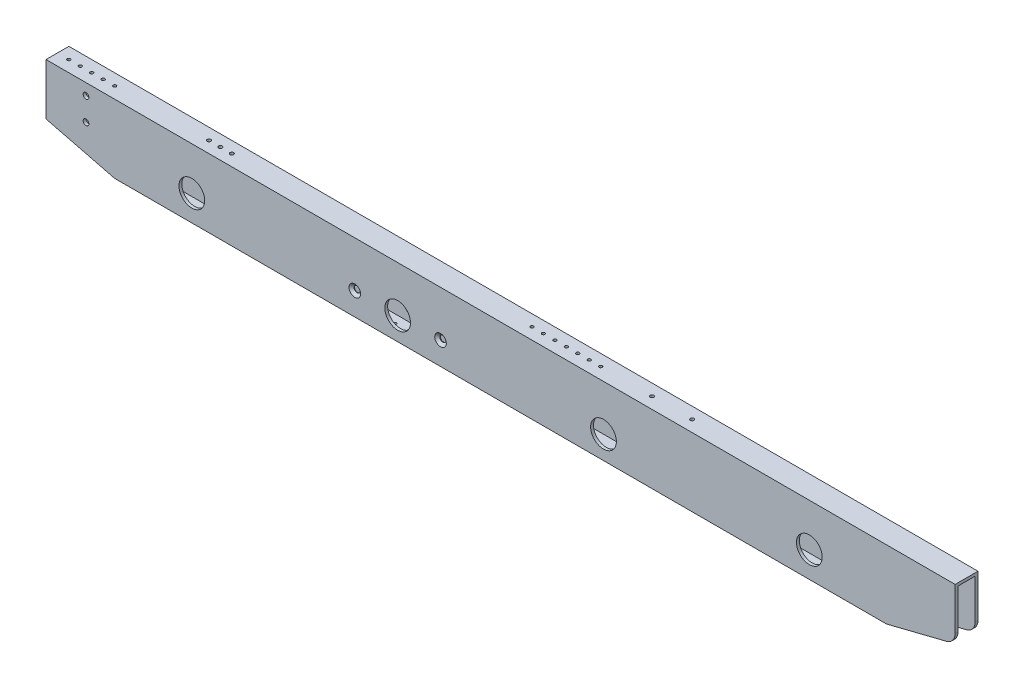
SolidWorks part; units mm, degrees
ref_plane "Front Plane" through (0, 0, 0) normal (0, 0, 1) x (1, 0, 0)
ref_plane "Top Plane" through (0, 0, 0) normal (0, 1, 0) x (1, 0, 0)
ref_plane "Right Plane" through (0, 0, 0) normal (1, 0, 0) x (0, 0, -1)
sketch "Sketch1" plane through (0, 0, 0) normal (0, 0, 1) x (1, 0, 0)
  line L0 (0, -12.7) -> (-342.9, -9.525) construction
  line L1 (-504.825, 38.1) -> (504.825, 38.1)
  line L2 (-504.825, 38.1) -> (-504.825, -38.1)
  line L3 (-504.825, -38.1) -> (504.825, -38.1)
  line L4 (504.825, 38.1) -> (504.825, -38.1)
  line L5 (-504.825, 38.1) -> (504.825, -38.1) construction
  line L6 (-504.825, -38.1) -> (504.825, 38.1) construction
  line L7 (-504.825, -38.1) -> (504.825, -38.1) construction
  line L8 (-504.825, -38.1) -> (-504.825, -12.7) construction
  line L9 (-327.025, -63.5) -> (327.025, -63.5) construction
  line L10 (-504.825, -12.7) -> (504.825, -12.7) construction
  line L11 (504.825, -38.1) -> (504.825, -12.7) construction
  line L12 (0, -12.7) -> (342.9, -9.525) construction
  line L13 (-114.3, -12.7) -> (114.3, -12.7) construction
  circle A0 centre (114.3, -12.7) radius 14.2875
  circle A1 centre (-342.9, -9.525) radius 14.2875
  circle A2 centre (342.9, -9.525) radius 14.2875
  circle A3 centre (-114.3, -12.7) radius 14.2875
  point P0 (0, 0)
  dimension "D5" = 28.575
  dimension "D4" = 28.575
  dimension "D8" = 228.6
  dimension "D6" = 228.6
  dimension "D7" = 228.6
  dimension "D1" = 76.2
  dimension "D2" = 1009.65
  dimension "D3" = 25.4
extrude "Boss-Extrude2" add sketch "Sketch1" along normal mid plane 25.4
sketch "Sketch3" plane through (504.825, 0, 0) normal (1, 0, 0) x (0, 0, -1)
  line L8 (9.525, -34.925) -> (9.525, 34.925)
  line L9 (9.525, 34.925) -> (-9.525, 34.925)
  line L10 (-9.525, 34.925) -> (-9.525, -34.925)
  line L11 (-9.525, -34.925) -> (9.525, -34.925)
  line L12 (9.525, -34.925) -> (9.525, 34.925)
  line L13 (9.525, 34.925) -> (-9.525, 34.925)
  line L14 (-9.525, 34.925) -> (-9.525, -34.925)
  line L15 (-9.525, -34.925) -> (9.525, -34.925)
  dimension "D1" = 3.175
extrude "Cut-Extrude2" cut sketch "Sketch3" against normal through all
sketch "Sketch4" plane through (0, 0, 12.7) normal (0, 0, 1) x (1, 0, 0)
  line L0 (-504.825, -38.1) -> (-504.825, -19.05)
  line L1 (-504.825, 38.1) -> (-504.825, -38.1) construction
  line L2 (-504.825, -19.05) -> (-428.625, -38.1)
  line L3 (-504.825, -38.1) -> (504.825, -38.1) construction
  line L4 (-428.625, -38.1) -> (-504.825, -38.1)
  line L5 (0, -38.1) -> (0, 38.1) construction
  line L6 (504.825, 38.1) -> (-504.825, 38.1) construction
  line L7 (428.625, -38.1) -> (504.825, -38.1)
  line L8 (504.825, -38.1) -> (504.825, -19.05)
  line L9 (504.825, -19.05) -> (428.625, -38.1)
  dimension "D1" = 19.05
  dimension "D2" = 76.2
  dimension "D3" = 57.15
extrude "Cut-Extrude3" cut sketch "Sketch4" against normal through all
fillet "Fillet1" radius 12.7 2 edges at (504.825, -19.05, -11.1125) (504.825, -19.05, 11.1125)
sketch "Sketch9" plane through (0, 38.1, 0) normal (0, 1, 0) x (1, 0, 0)
  line L0 (-504.825, -12.7) -> (-504.825, 12.7) construction
  line L1 (0, -12.7) -> (0, 12.7) construction
  line L2 (504.825, -12.7) -> (-504.825, -12.7) construction
  line L3 (504.825, 12.7) -> (-504.825, 12.7) construction
  circle A0 centre (-492.125, 0) radius 1.7272
  circle A1 centre (-441.325, 0) radius 1.7272
  circle A2 centre (-479.425, 0) radius 1.7272
  circle A3 centre (-466.725, 0) radius 1.7272
  circle A4 centre (-454.025, 0) radius 1.7272
  point P2 (-504.825, 0)
  dimension "D1" = 3.4544
  dimension "D2" = 12.7
  dimension "D3" = 4
  dimension "D4" = 2
extrude "Cut-Extrude5" cut sketch "Sketch9" against normal blind 6.35
sketch "Sketch12" plane through (0, 38.1, 0) normal (0, 1, 0) x (1, 0, 0)
  line L0 (504.825, -12.7) -> (504.825, 12.7) construction
  circle A0 centre (98.425, 0) radius 1.7272
  circle A1 centre (85.725, 0) radius 1.7272
  circle A2 centre (73.025, 0) radius 1.7272
  circle A3 centre (60.325, 0) radius 1.7272
  circle A4 centre (47.625, 0) radius 1.7272
  circle A5 centre (34.925, 0) radius 1.7272
  circle A6 centre (22.225, 0) radius 1.7272
  point P2 (504.825, 0)
  dimension "D1" = 3.4544
  dimension "D2" = 406.4
  dimension "D3" = 7
extrude "Cut-Extrude8" cut sketch "Sketch12" against normal blind 5.08
hole_wizard "CSK for 1/4 Flat Head Machine Screw (100)1" positions "Sketch14" profile "Sketch13" countersink size "1/4" standard "ANSI Inch" end condition through all
sketch "Sketch14" plane through (0, 0, 12.7) normal (0, 0, 1) x (1, 0, 0)
  circle A1 centre (-114.3, -12.7) radius 14.2875 construction
  point P0 (-66.675, -12.7)
  point P2 (-161.925, -12.7)
  dimension "D4" = 47.625
  dimension "D3" = 47.625
sketch "Sketch13" plane through (-66.675, -12.7, 12.7) normal (1, 0, 0) x (0, -1, 0)
  line L0 (0, 0) -> (0, 25.4)
  line L1 (0, 25.4) -> (3.3782, 25.4)
  line L2 (3.3782, 25.4) -> (3.3782, 2.5682)
  line L3 (3.3782, 2.5682) -> (6.4389, 0)
  line L5 (6.4389, 0) -> (0, 0)
  line L6 (-3.3782, 2.5682) -> (-6.4389, 0) construction
  line L11 (0, -6.35) -> (0, 107.95) construction
  dimension "Thru Hole Dia." = 6.7564
  dimension "Thru Hole Depth" = 25.4
  dimension "Near C'Sink Dia." = 12.8778
  dimension "Near C'Sink Angle" = 100
sketch "Sketch15" plane through (0, -38.1, 0) normal (0, -1, 0) x (-1, 0, 0)
  line L0 (428.625, 12.7) -> (428.625, -12.7) construction
  circle A0 centre (415.925, 0) radius 1.7272
  circle A1 centre (396.875, 0) radius 1.7272
  circle A2 centre (377.825, 0) radius 1.7272
  circle A3 centre (358.775, 0) radius 1.7272
  circle A4 centre (339.725, 0) radius 1.7272
  circle A5 centre (320.675, 0) radius 1.7272
  circle A6 centre (301.625, 0) radius 1.7272
  circle A7 centre (282.575, 0) radius 1.7272
  circle A8 centre (263.525, 0) radius 1.7272
  circle A9 centre (244.475, 0) radius 1.7272
  circle A10 centre (225.425, 0) radius 1.7272
  circle A11 centre (206.375, 0) radius 1.7272
  circle A12 centre (187.325, 0) radius 1.7272
  circle A13 centre (168.275, 0) radius 1.7272
  circle A14 centre (149.225, 0) radius 1.7272
  circle A15 centre (130.175, 0) radius 1.7272
  circle A16 centre (111.125, 0) radius 1.7272
  circle A17 centre (92.075, 0) radius 1.7272
  circle A18 centre (73.025, 0) radius 1.7272
  circle A19 centre (53.975, 0) radius 1.7272
  circle A20 centre (34.925, 0) radius 1.7272
  circle A21 centre (15.875, 0) radius 1.7272
  circle A22 centre (-3.175, 0) radius 1.7272
  circle A23 centre (-22.225, 0) radius 1.7272
  circle A24 centre (-41.275, 0) radius 1.7272
  circle A25 centre (-60.325, 0) radius 1.7272
  point P2 (428.625, 0)
  dimension "D1" = 3.4544
  dimension "D2" = 12.7
  dimension "D3" = 26
extrude "Cut-Extrude9" cut sketch "Sketch15" against normal blind 6.35
sketch "Sketch16" plane through (0, 0, -12.7) normal (0, 0, -1) x (-1, 0, 0)
  circle A0 centre (114.3, -12.7) radius 17.4625
  dimension "D1" = 34.925
extrude "Cut-Extrude10" cut sketch "Sketch16" against normal blind 3.81
hole_wizard "1/4 (0.25) Diameter Hole1" positions "Sketch19" profile "Sketch18" hole size "1/4" standard "ANSI Inch" end condition through all
sketch "Sketch19" plane through (0, 0, 12.7) normal (0, 0, 1) x (1, 0, 0)
  line L0 (-504.825, 38.1) -> (-504.825, -19.05) construction
  line L1 (-479.425, -25.4) -> (-479.425, 3.7361) construction
  line L2 (-428.625, -38.1) -> (-504.825, -19.05) construction
  line L5 (504.825, 38.1) -> (-504.825, 38.1) construction
  point P0 (-460.375, 25.4)
  point P2 (-460.375, 0)
  dimension "D1" = 19.05
  dimension "D2" = 25.4
  dimension "D3" = 25.4
  dimension "D4" = 12.7
sketch "Sketch18" plane through (-460.375, 25.4, 12.7) normal (1, 0, 0) x (0, -1, 0)
  line L0 (0, 0) -> (0, 25.4)
  line L1 (0, 25.4) -> (3.175, 25.4)
  line L2 (3.175, 25.4) -> (3.175, 0)
  line L5 (3.175, 0) -> (0, 0)
  line L11 (0, -6.35) -> (0, 107.95) construction
  dimension "Thru Hole Dia." = 6.35
  dimension "Thru Hole Depth" = 25.4
hole_wizard "#10-32 Tapped Hole2" positions "Sketch21" profile "Sketch20" tap size "#10-32" standard "ANSI Inch"
sketch "Sketch21" plane through (0, 38.1, 0) normal (0, 1, 0) x (1, 0, 0)
  circle A0 centre (60.325, 0) radius 1.7272 construction
  point P0 (155.575, 0)
  point P2 (200.025, 0)
  dimension "D1" = 95.25
  dimension "D2" = 44.45
cosmetic thread "Hole Thread1" parameters "D1"=3.175, "D2"=4.826
cosmetic thread "Hole Thread2" parameters "D1"=3.175, "D2"=4.826
sketch "Sketch20" plane through (155.575, 38.1, 0) normal (1, 0, 0) x (0, 0, 1)
  line L0 (0, 0) -> (0, 14.9293)
  line L1 (0, 14.9293) -> (2.0193, 13.716)
  line L2 (2.0193, 13.716) -> (2.0193, 0)
  line L5 (2.0193, 0) -> (0, 0)
  line L10 (0, 14.9293) -> (-2.0193, 13.716) construction
  line L11 (0, -6.35) -> (0, 107.95) construction
  dimension "Tap Drill Dia." = 4.0386
  dimension "Tap Drill Depth" = 13.716
  dimension "Drill Angle" = 118
hole_wizard "#10-32 Tapped Hole3" positions "Sketch23" profile "Sketch22" tap size "#10-32" standard "ANSI Inch" end condition through all
sketch "Sketch23" plane through (0, 38.1, 0) normal (0, 1, 0) x (1, 0, 0)
  line L0 (-504.825, -12.7) -> (-504.825, 12.7) construction
  point P0 (-336.55, 0)
  point P2 (-311.15, 0)
  point P4 (-323.85, 0)
  dimension "D1" = 168.275
  dimension "D2" = 12.7
  dimension "D3" = 12.7
sketch "Sketch22" plane through (-336.55, 38.1, 0) normal (1, 0, 0) x (0, 0, 1)
  line L0 (0, 0) -> (0, 76.2)
  line L1 (0, 76.2) -> (2.0193, 76.2)
  line L2 (2.0193, 76.2) -> (2.0193, 0)
  line L5 (2.0193, 0) -> (0, 0)
  line L11 (0, -6.35) -> (0, 107.95) construction
  dimension "Thread Major Dia." = 4.0386
  dimension "Thru Tap Drill Depth" = 76.2
